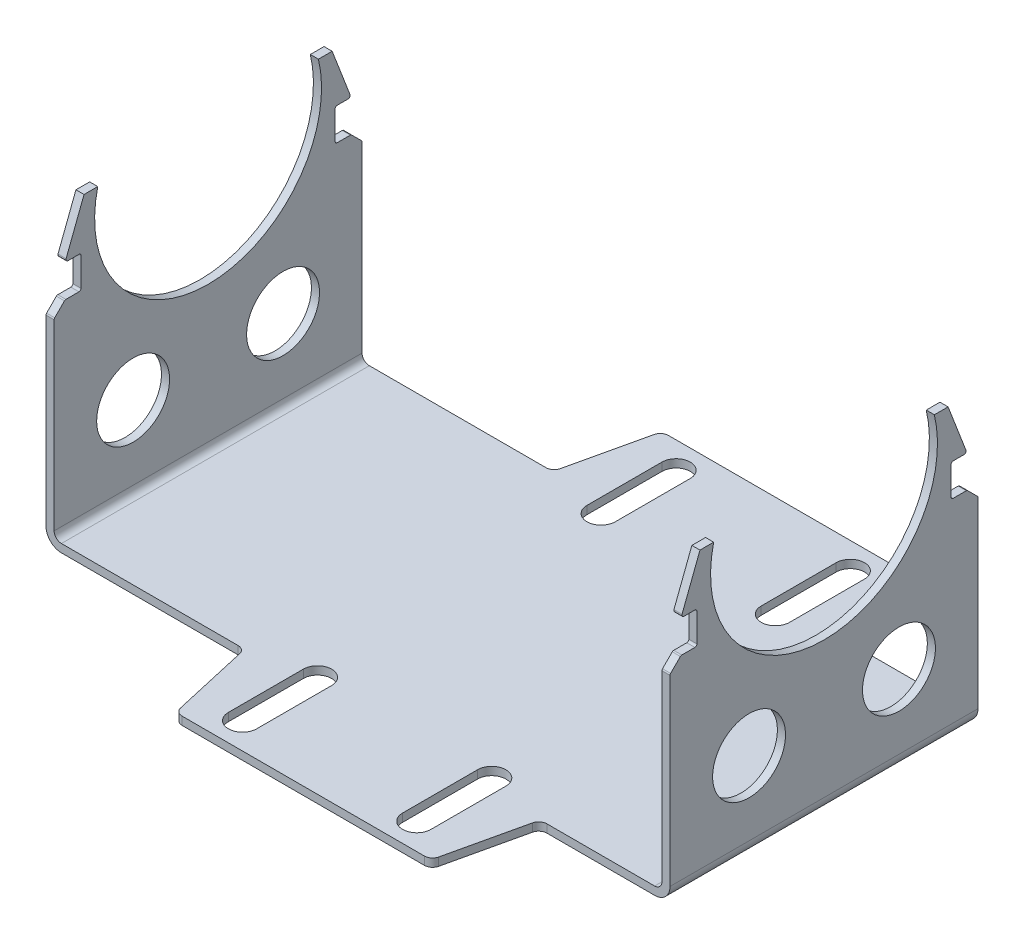
SolidWorks part; units mm, degrees
ref_plane "Спереди" through (0, 0, 0) normal (0, 0, 1) x (1, 0, 0)
ref_plane "Сверху" through (0, 0, 0) normal (0, 1, 0) x (1, 0, 0)
ref_plane "Справа" through (0, 0, 0) normal (1, 0, 0) x (0, 0, -1)
sketch "Эскиз1" plane through (0, 0, 0) normal (0, 1, 0) x (1, 0, 0)
  line L0 (52, 0) -> (115, 0)
  line L4 (152, 22) -> (120, 22)
  line L6 (47, 22) -> (-2, 22)
  line L10 (52, 120) -> (47, 98)
  line L12 (115, 0) -> (120, 22)
  line L13 (52, 0) -> (47, 22)
  line L14 (115, 120) -> (120, 98)
  line L15 (47, 98) -> (-2, 98)
  line L16 (152, 98) -> (120, 98)
  line L17 (52, 120) -> (115, 120)
  line L18 (-2, 98) -> (-2, 22)
  line L20 (152, 98) -> (152, 22)
extrude "Бобышка-Вытянуть1" add sketch "Эскиз1" along normal blind 2
sketch "Эскиз3" plane through (0, 2, 0) normal (0, 1, 0) x (1, 0, 0)
  line L0 (-2, 98) -> (-2, 22)
  line L1 (-2, 22) -> (0, 22)
  line L2 (-2, 22) -> (47, 22) construction
  line L3 (0, 22) -> (0, 98)
  line L4 (47, 98) -> (-2, 98) construction
  line L5 (0, 98) -> (-2, 98)
  line L6 (152, 98) -> (152, 22)
  line L7 (152, 22) -> (150, 22)
  line L8 (120, 22) -> (152, 22) construction
  line L9 (150, 22) -> (150, 98)
  line L10 (152, 98) -> (120, 98) construction
  line L11 (150, 98) -> (152, 98)
extrude "Бобышка-Вытянуть2" add sketch "Эскиз3" along normal blind 70
sketch "Эскиз5" plane through (-2, 0, 0) normal (-1, 0, 0) x (0, 0, 1)
  line L2 (-95.2997, 59.8214) -> (-91.3612, 59.8214)
  line L3 (-91.3612, 59.8214) -> (-91.3612, 51.8214)
  line L4 (-90.6148, 72) -> (-95.2997, 59.8214)
  line L5 (-91.3612, 51.8214) -> (-95.2997, 51.8214)
  line L6 (-95.2997, 51.8214) -> (-98, 49.1211)
  line L7 (-98, 72) -> (-98, 0) construction
  line L12 (-90.6148, 72) -> (-98, 72)
  line L13 (-98, 72) -> (-98, 49.1211)
  line L15 (-22, 72) -> (-22, 49.1211)
  line L16 (-29.3852, 72) -> (-22, 72)
  line L17 (-24.7003, 51.8214) -> (-22, 49.1211)
  line L18 (-28.6388, 51.8214) -> (-24.7003, 51.8214)
  line L19 (-29.3852, 72) -> (-24.7003, 59.8214)
  line L20 (-28.6388, 59.8214) -> (-28.6388, 51.8214)
  line L21 (-24.7003, 59.8214) -> (-28.6388, 59.8214)
  circle A2 centre (-60, 65.4774) radius 28
extrude "Вырез-Вытянуть1" cut sketch "Эскиз5" against normal through all
fillet "Скругление1" radius 0.5 20 edges at (151, 49.1211, -22) (151, 51.8214, -24.7003) (151, 51.8214, -28.6388) (151, 59.8214, -28.6388) (151, 59.8214, -24.7003) (151, 49.1211, -98) (151, 51.8214, -95.2997) (151, 51.8214, -91.3612) (151, 59.8214, -91.3612) (151, 59.8214, -95.2997) (-1, 49.1211, -98) (-1, 51.8214, -95.2997) (-1, 51.8214, -91.3612) (-1, 59.8214, -91.3612) (-1, 59.8214, -95.2997) (-1, 49.1211, -22) (-1, 51.8214, -24.7003) (-1, 51.8214, -28.6388) (-1, 59.8214, -28.6388) (-1, 59.8214, -24.7003)
fillet "Скругление2" radius 1.8 2 edges at (150, 2, -60) (0, 2, -60)
fillet "Скругление3" radius 3.8 2 edges at (-2, 0, -60) (152, 0, -60)
fillet "Скругление4" radius 2 8 edges at (47, 1, -22) (52, 1, 0) (115, 1, 0) (120, 1, -22) (120, 1, -98) (115, 1, -120) (52, 1, -120) (47, 1, -98)
sketch "Эскиз6" plane through (-2, 0, 0) normal (-1, 0, 0) x (0, 0, 1)
  line L0 (-22, 48.914) -> (-22, 3.8) construction
  line L1 (-98, 48.914) -> (-98, 3.8) construction
  line L2 (-22, 0) -> (-98, 0) construction
  circle A0 centre (-78.5, 22) radius 9
  circle A1 centre (-41.5, 22) radius 9
  dimension "D1" = 18
  dimension "D2" = 18
  dimension "D3" = 19.5
  dimension "D4" = 19.5
  dimension "D6" = 22
  dimension "D5" = 22
extrude "Вырез-Вытянуть2" cut sketch "Эскиз6" against normal through all
sketch "Эскиз7" plane through (0, 2, 0) normal (0, 1, 0) x (1, 0, 0)
  line L0 (1.8, 60) -> (148.2, 60) construction
  line L2 (65.5, 25) -> (65.5, 6.5)
  line L3 (108.5, 25) -> (108.5, 6.5)
  line L4 (58.5, 25) -> (58.5, 6.5)
  line L5 (1.8, 98) -> (1.8, 22) construction
  line L6 (148.2, 22) -> (148.2, 98) construction
  line L9 (101.5, 25) -> (101.5, 6.5)
  line L10 (101.5, 95) -> (101.5, 113.5)
  line L11 (58.5, 95) -> (58.5, 113.5)
  line L12 (108.5, 95) -> (108.5, 113.5)
  line L13 (65.5, 95) -> (65.5, 113.5)
  arc A0 (101.5, 6.5) -> (108.5, 6.5) centre (105, 6.5) ccw
  arc A1 (108.5, 25) -> (101.5, 25) centre (105, 25) ccw
  arc A2 (58.5, 25) -> (65.5, 25) centre (62, 25) cw
  arc A3 (65.5, 6.5) -> (58.5, 6.5) centre (62, 6.5) cw
  arc A4 (65.5, 113.5) -> (58.5, 113.5) centre (62, 113.5) ccw
  arc A5 (58.5, 95) -> (65.5, 95) centre (62, 95) ccw
  arc A6 (108.5, 95) -> (101.5, 95) centre (105, 95) cw
  arc A7 (101.5, 113.5) -> (108.5, 113.5) centre (105, 113.5) cw
extrude "Вырез-Вытянуть3" cut sketch "Эскиз7" against normal blind 10
